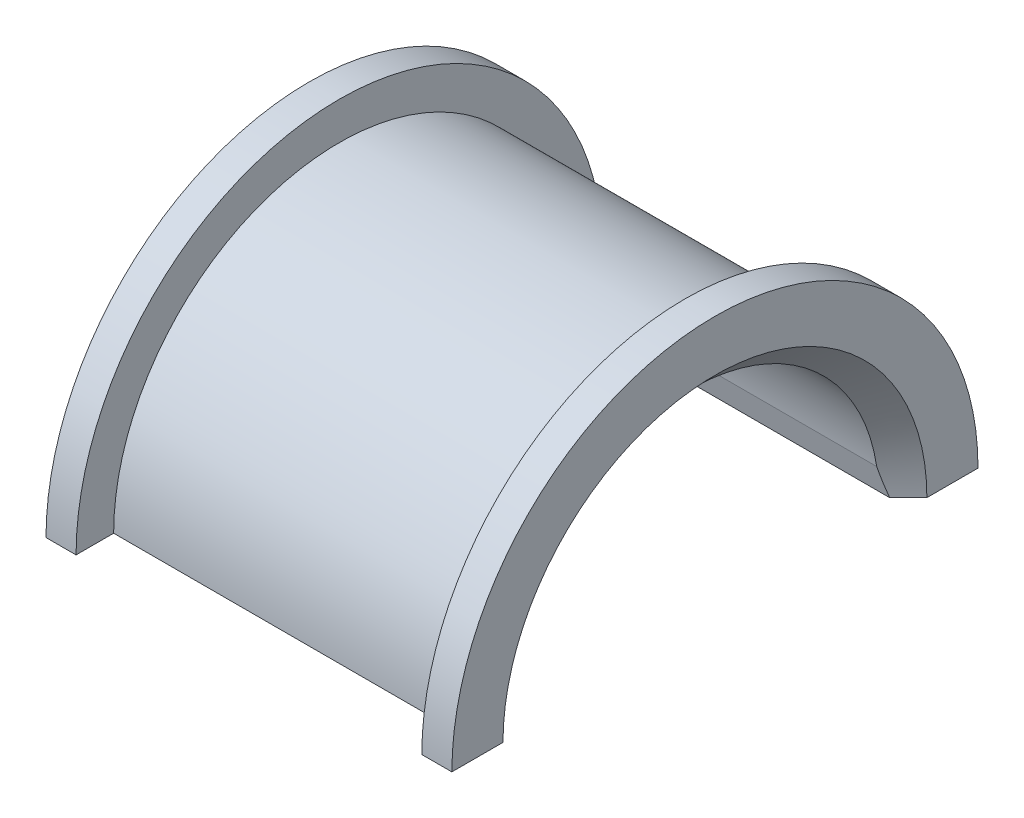
SolidWorks part; units mm, degrees
material "Алюминиевая бронза"
ref_plane "Спереди" through (0, 0, 0) normal (0, 0, 1) x (1, 0, 0)
ref_plane "Сверху" through (0, 0, 0) normal (0, 1, 0) x (1, 0, 0)
ref_plane "Справа" through (0, 0, 0) normal (1, 0, 0) x (0, 0, -1)
sketch "Эскиз1" plane through (0, 0, 0) normal (0, 0, 1) x (1, 0, 0)
  line L0 (-27.196, 0) -> (51.6886, 0) construction
  line L1 (0, 14.1) -> (0, 17.5)
  line L2 (0, 17.5) -> (2, 17.5)
  line L3 (2, 17.5) -> (2, 15)
  line L4 (2, 15) -> (25, 15)
  line L5 (25, 15) -> (25, 17.5)
  line L6 (25, 17.5) -> (27, 17.5)
  line L7 (27, 17.5) -> (27, 14.1)
  line L8 (25.4, 12.5) -> (1.6, 12.5)
  line L9 (1.6, 12.5) -> (0, 14.1)
  line L10 (27, 14.1) -> (25.4, 12.5)
  point P3 (0, 12.5)
  point P11 (27, 12.5)
  dimension "D1" = 25
  dimension "D2" = 30
  dimension "D3" = 35
  dimension "D4" = 23
  dimension "D5" = 2
  dimension "D6" = 27
  dimension "D7" = 1.6
  dimension "D8" = 45
  dimension "D9" = 1.6
  dimension "D10" = 45
revolve "Повернуть1" add sketch "Эскиз1" angle 180 mid plane about L0
sketch "Эскиз2" plane through (0, 0, 0) normal (-1, 0, 0) x (0, 0, 1)
  line L0 (-19.8055, 0) -> (20.1791, 0) construction
  line L1 (0, -19.8755) -> (0, 19.2216) construction
  line L2 (12.8599, 0) -> (12.3599, 1.866)
  line L3 (12.3599, 1.866) -> (12.3599, 0)
  line L4 (12.3599, 0) -> (12.8599, 0)
  line L5 (-12.8599, 0) -> (-12.3599, 1.866)
  line L6 (-12.3599, 1.866) -> (-12.3599, 0)
  line L7 (-12.3599, 0) -> (-12.8599, 0)
  arc A1 (12.5, 0) -> (-12.5, 0) centre (0, 0) ccw construction
  dimension "D1" = 75
  dimension "D2" = 0.5
extrude "Вырез-Вытянуть1" cut sketch "Эскиз2" against normal through all
